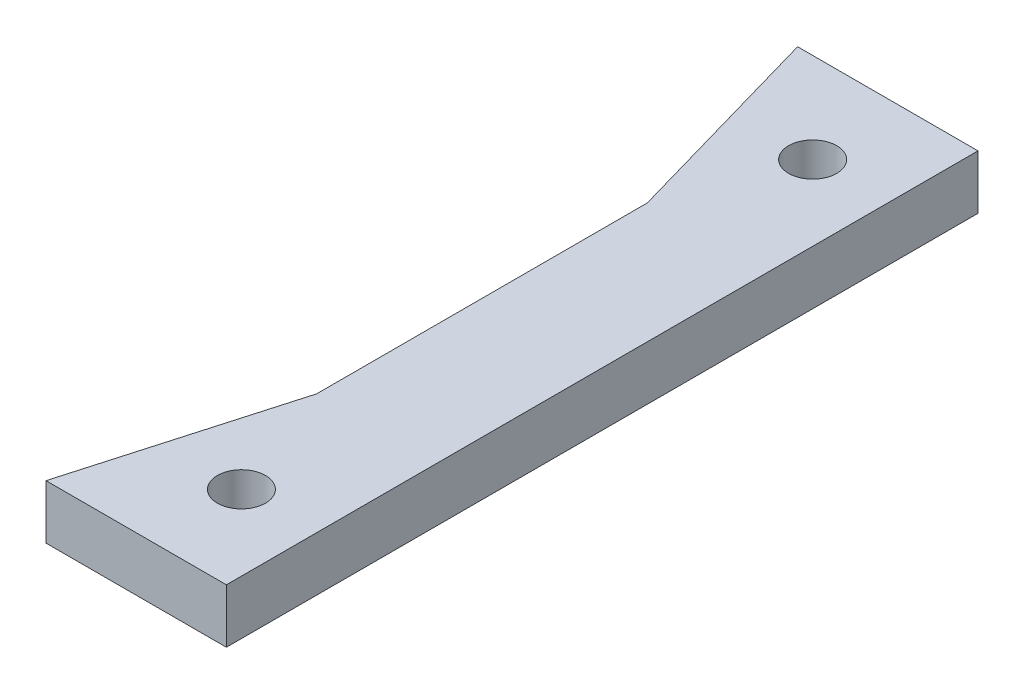
SolidWorks part; units mm, degrees
ref_plane "Front Plane" through (0, 0, 0) normal (0, 0, 1) x (1, 0, 0)
ref_plane "Top Plane" through (0, 0, 0) normal (0, 1, 0) x (1, 0, 0)
ref_plane "Right Plane" through (0, 0, 0) normal (1, 0, 0) x (0, 0, -1)
sketch "Sketch1" plane through (0, 0, 0) normal (0, 1, 0) x (1, 0, 0)
  line L0 (0, 28.6261) -> (0, -32.6516) construction
  line L1 (-64.4801, 0) -> (50.9921, 0) construction
  line L2 (-20, -27.5) -> (-20, 27.5)
  line L3 (-20, 27.5) -> (-30, 62.5)
  line L9 (-20, -27.5) -> (-30, -62.5)
  line L10 (-30, 62.5) -> (0, 62.5)
  line L11 (-30, -62.5) -> (0, -62.5)
  line L12 (0, 62.5) -> (10, 62.5)
  line L13 (10, 62.5) -> (10, -62.5)
  line L14 (10, -62.5) -> (0, -62.5)
  line L15 (0, 62.5) -> (0, -62.5)
  circle A0 centre (-12.5, 47.5) radius 4
  circle A3 centre (-12.5, -47.5) radius 4
  point P4 (0, -62.5)
  point P9 (-25, 45)
  point P16 (0, 62.5)
  point P24 (-20, 0)
  dimension "D3" = 8
  dimension "D7" = 15
  dimension "D1" = 30
  dimension "D2" = 62.5
  dimension "D4" = 17.5
  dimension "D5" = 12.5
  dimension "D6" = 25
  dimension "D8" = 10
  dimension "D9" = 35
extrude "Boss-Extrude1" add sketch "Sketch1" along normal blind 9 contours L15 L10 L3 L2 L9 L11 A0 A3
